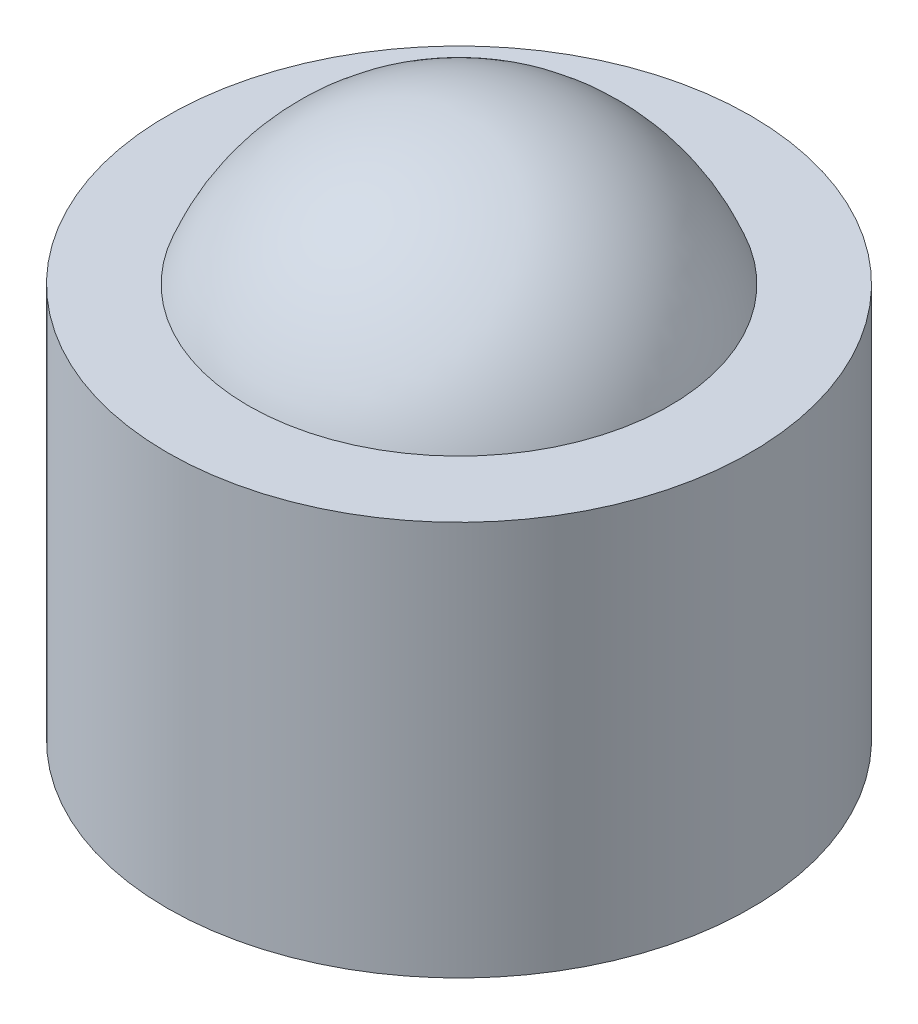
SolidWorks part; units mm, degrees
ref_plane "前视基准面" through (0, 0, 0) normal (0, 0, 1) x (1, 0, 0)
ref_plane "上视基准面" through (0, 0, 0) normal (0, 1, 0) x (1, 0, 0)
ref_plane "右视基准面" through (0, 0, 0) normal (1, 0, 0) x (0, 0, -1)
sketch "草图1" plane through (0, 0, 0) normal (0, 0, 1) x (1, 0, 0)
  line L0 (0, 0) -> (0, 5.8956) construction
  line L1 (0, 4.32) -> (0, -4.32)
  arc A0 (0, -4.32) -> (0, 4.32) centre (0, 0) ccw
revolve "旋转2" add sketch "草图1" angle 360 about L0
sketch "草图2" plane through (0, 0, 0) normal (0, 0, 1) x (1, 0, 0)
  line L4 (5.6, -6.056) -> (0, -6.056)
  line L5 (0, -6.056) -> (0, 1.52)
  line L6 (5.6, -6.056) -> (5.6, 1.52)
  line L7 (5.6, 1.52) -> (0, 1.52)
  dimension "D1" = 7.576
  dimension "D2" = 1.52
  dimension "D3" = 5.6
revolve "旋转3" add sketch "草图2" angle 360 about L5
scale "Масштаб1" scale about centroid uniform scaling yes scale factor 2.7
scale "Масштаб2" bodies to scale 103 scale about centroid uniform scaling yes scale factor 0.72
sketch "Эскиз1" plane through (0, -10.0861, 0) normal (0, -1, 0) x (1, 0, 0)
  point P0 (0, 0)
